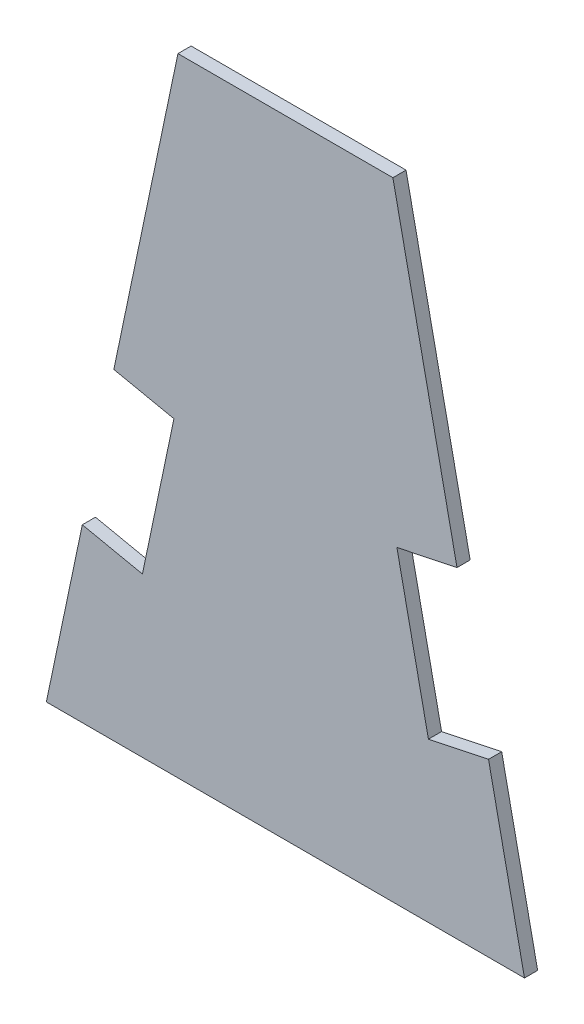
SolidWorks part; units mm, degrees
ref_plane "Front Plane" through (0, 0, 0) normal (0, 0, 1) x (1, 0, 0)
ref_plane "Top Plane" through (0, 0, 0) normal (0, 1, 0) x (1, 0, 0)
ref_plane "Right Plane" through (0, 0, 0) normal (1, 0, 0) x (0, 0, -1)
sketch "Sketch1" plane through (0, 0, 0) normal (0, 0, 1) x (1, 0, 0)
  line L0 (0, 0) -> (109, 0)
  line L1 (109, 0) -> (100.8015, 39.0793)
  line L2 (100.8015, 39.0793) -> (87.0998, 36.2048)
  line L3 (87.0998, 36.2048) -> (79.9136, 70.4591)
  line L4 (79.9136, 70.4591) -> (93.6153, 73.3336)
  line L5 (93.6153, 73.3336) -> (79, 143)
  line L6 (79, 143) -> (30, 143)
  line L7 (30, 143) -> (15.3847, 73.3336)
  line L8 (54.5, 143) -> (54.5, 0) construction
  line L9 (29.0864, 70.4591) -> (15.3847, 73.3336)
  line L10 (21.9002, 36.2048) -> (29.0864, 70.4591)
  line L11 (8.1985, 39.0793) -> (21.9002, 36.2048)
  line L12 (8.1985, 39.0793) -> (0, 0)
  dimension "D1" = 109
  dimension "D2" = 143
  dimension "D3" = 14
  dimension "D4" = 39.93
  dimension "D5" = 35
  dimension "D6" = 49
extrude "Boss-Extrude1" add sketch "Sketch1" along normal blind 3 contours L5 L6 L7 L9 L10 L11 L12 L0 L1 L2 L3 L4
